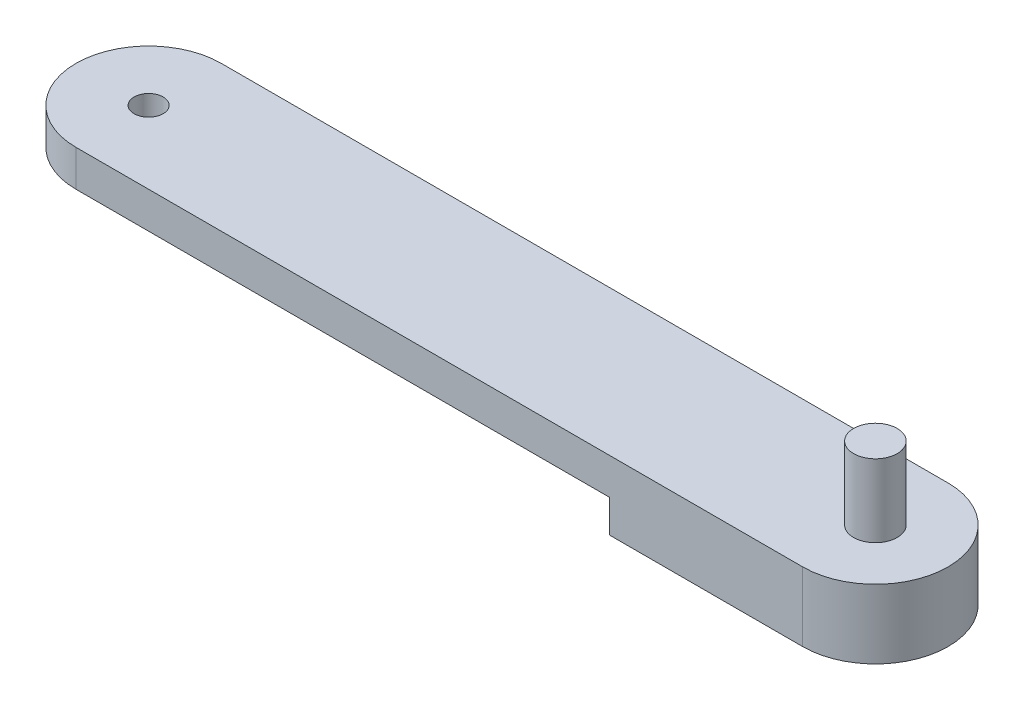
SolidWorks part; units mm, degrees
ref_plane "前视基准面" through (0, 0, 0) normal (0, 0, 1) x (1, 0, 0)
ref_plane "上视基准面" through (0, 0, 0) normal (0, 1, 0) x (1, 0, 0)
ref_plane "右视基准面" through (0, 0, 0) normal (1, 0, 0) x (0, 0, -1)
other "Configuration Table"
sketch "草图1" plane through (0, 0, 0) normal (0, 1, 0) x (1, 0, 0)
  line L0 (0, 0) -> (100, 0) construction
  line L1 (0, 10) -> (100, 10)
  line L2 (0, -10) -> (100, -10)
  arc A0 (0, 10) -> (0, -10) centre (0, 0) ccw
  arc A1 (100, -10) -> (100, 10) centre (100, 0) ccw
  circle A2 centre (0, 0) radius 2
  point P3 (50, 0)
  dimension "D3" = 4
  dimension "D1" = 100
  dimension "D2" = 20
extrude "凸台-拉伸1" add sketch "草图1" along normal blind 5
sketch "草图2" plane through (0, 5, 0) normal (0, 1, 0) x (1, 0, 0)
  circle A0 centre (100, 0) radius 3
extrude "凸台-拉伸2" add sketch "草图2" along normal blind 10
sketch "草图3" plane through (0, 0, 0) normal (0, -1, 0) x (1, 0, 0)
  line L0 (100, -10) -> (0, -10) construction
  line L1 (100, 10) -> (73.4078, 10)
  line L3 (100, -10) -> (73.4078, -10)
  line L4 (73.4078, 10) -> (73.4078, -10)
  arc A0 (100, -10) -> (100, 10) centre (100, 0) ccw
extrude "凸台-拉伸3" add sketch "草图3" along normal blind 4.5
sketch "草图4" plane through (0, -4.5, 0) normal (0, -1, 0) x (1, 0, 0)
  line L1 (79.8492, 2.2886) -> (99.6902, 3.2362)
  line L2 (79.8492, -2.2886) -> (99.6902, -3.2362)
  arc A0 (99.6902, -3.2362) -> (99.6902, 3.2362) centre (100, 0) ccw
  arc A1 (79.8492, 2.2886) -> (79.8492, -2.2886) centre (79.8492, 0) ccw
extrude "切除-拉伸1" cut sketch "草图4" against normal blind 4.5
